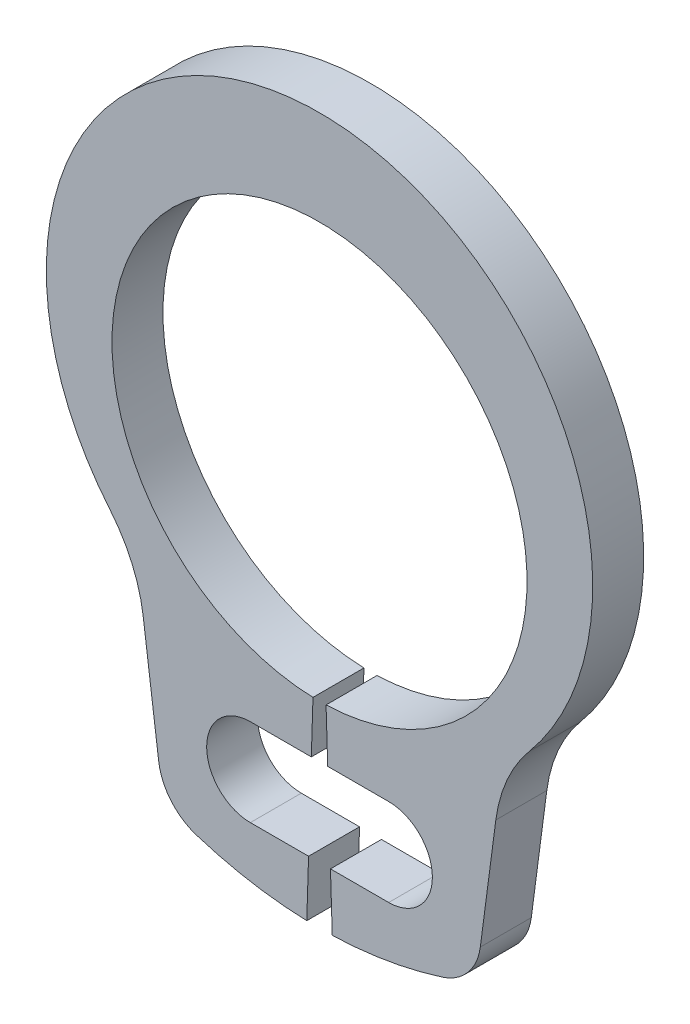
SolidWorks part; units mm, degrees
ref_plane "Plane1" through (0, 0, 0) normal (0, 0, 1) x (1, 0, 0)
ref_plane "Plane2" through (0, 0, 0) normal (0, 1, 0) x (1, 0, 0)
ref_plane "Plane3" through (0, 0, 0) normal (1, 0, 0) x (0, 0, -1)
other "Configuration Table"
sketch "Clipboard" plane through (0, 0, 0) normal (0, 0, 1) x (1, 0, 0)
  line L0 (0, 0) -> (1.3, 0)
  line L1 (0, 0) -> (0, 0.65)
  line L2 (0, 0) -> (0, -2.7)
  circle A0 centre (0, 0) radius 0.6
  circle A1 centre (0, 0) radius 3
  dimension "HoleDia" = 1.2
  dimension "ShaftDia" = 6
  dimension "LargeSection" = 1.3
  dimension "SmallSection" = 0.65
  dimension "LugSection" = 2.7
sketch "BodySke" plane through (0, 0, 0) normal (0, 0, 1) x (1, 0, 0)
  line L0 (-1.5431, 0) -> (1.5431, 0) construction
  line L1 (0, 0) -> (0, 4.15) construction
  line L2 (0.0899, -2.8486) -> (0.175, -5.5472)
  line L3 (-0.0899, -2.8486) -> (-0.175, -5.5472)
  line L4 (0, 0) -> (4.4489, -3.318) construction
  line L5 (0, 0) -> (-4.4489, -3.318) construction
  line L7 (2.4213, -3.0511) -> (2.2083, -4.669)
  line L8 (-2.4213, -3.0511) -> (-2.2083, -4.669)
  circle A0 centre (0, 0) radius 2.85 construction
  arc A1 (0.0899, -2.8486) -> (-0.0899, -2.8486) centre (0, 0) ccw
  arc A2 (2.8056, -2.0925) -> (-2.8056, -2.0925) centre (0, 0.3983) ccw construction
  arc A3 (0.175, -5.5472) -> (1.6935, -5.2853) centre (0, 0) ccw
  arc A4 (2.8793, -2.0069) -> (2.4213, -3.0511) centre (4.4489, -3.318) ccw
  arc A5 (-2.4213, -3.0511) -> (-2.8793, -2.0069) centre (-4.4489, -3.318) ccw
  arc A6 (-1.6935, -5.2853) -> (-0.175, -5.5472) centre (0, 0) ccw
  arc A7 (2.8793, -2.0069) -> (-2.8793, -2.0069) centre (0, 0.3983) ccw
  arc A8 (-2.353, -3.5691) -> (2.353, -3.5691) centre (0, 0) ccw construction
  circle A9 centre (0.95, -4.1681) radius 0.6
  circle A10 centre (-0.95, -4.1681) radius 0.6
  arc A11 (2.2083, -4.669) -> (1.6935, -5.2853) centre (1.4647, -4.5711) cw
  arc A12 (-2.2083, -4.669) -> (-1.6935, -5.2853) centre (-1.4647, -4.5711) ccw
  point P28 (2.1493, -5.1169)
  point P31 (-2.1493, -5.1169)
  dimension "HoleDia" = 1.2
  dimension "GrooveDia" = 5.7
  dimension "LugRad" = 5.55
  dimension "HoleOffsetRad" = 4.275
  dimension "D3" = 0.75
  dimension "LargeRad" = 4.15
  dimension "SmallRad" = 3.5
  dimension "SmallAngle" = 106.569
  dimension "D2" = 15
  dimension "HoleSpacing" = 1.9
  dimension "Gap" = 0.35
extrude "Body" add sketch "BodySke" against normal blind 0.7
sketch "NotSke" plane through (0, 0, 0) normal (0, 0, 1) x (1, 0, 0)
  line L0 (0.95, -3.5681) -> (0.95, -4.7681)
  line L1 (0.95, -4.7681) -> (-0.95, -4.7681)
  line L2 (-0.95, -4.7681) -> (-0.95, -3.5681)
  line L3 (-0.95, -3.5681) -> (0.95, -3.5681)
  circle A0 centre (0.95, -4.1681) radius 0.6 construction
  circle A1 centre (-0.95, -4.1681) radius 0.6 construction
extrude "Notch" cut sketch "NotSke" against normal through all
sketch "UnlSke" plane through (0, 0, 0) normal (0, 0, 1) x (1, 0, 0)
  line L0 (-1.9806, -5.1846) -> (-1.0171, -2.6623)
  line L1 (1.9806, -5.1846) -> (1.0171, -2.6623)
  arc A0 (1.0171, -2.6623) -> (-1.0171, -2.6623) centre (0, 0) ccw
  arc A1 (1.9806, -5.1846) -> (-1.9806, -5.1846) centre (0, 0) ccw
  arc A2 (0.175, -5.5472) -> (1.6935, -5.2853) centre (0, 0) ccw construction
  arc A3 (0.0899, -2.8486) -> (-0.0899, -2.8486) centre (0, 0) ccw construction
  circle A4 centre (-0.95, -4.1681) radius 0.6 construction
  circle A5 centre (0.95, -4.1681) radius 0.6 construction
extrude "Unlug" [suppressed] add sketch "UnlSke" against normal through all
equation "' \"ShaftDia@Clipboard\" = 3"
equation "' \"Thickness@Body\" = 0.4"
equation "' \"GrooveDia@BodySke\" = 2.8"
equation "' \"LugSection@Clipboard\" = 1.9"
equation "' \"LargeSection@Clipboard\" = 0.8"
equation "' \"HoleDia@Clipboard\" = 1.0"
equation "' \"ShaftDia@Clipboard\" = 10"
equation "' \"Thickness@Body\" = 1.0"
equation "' \"GrooveDia@BodySke\" = 9.6"
equation "' \"LugSection@Clipboard\" = 3.3"
equation "' \"LargeSection@Clipboard\" = 1.8"
equation "' \"HoleDia@Clipboard\" = 1.5"
equation "\"SmallSection@Clipboard\" = \"LargeSection@Clipboard\" * 0.5"
equation "\"Gap@BodySke\" =  \"Thickness@Body\" / 2"
equation "\"LargeRad@BodySke\" =  \"GrooveDia@BodySke\" / 2 +  \"LargeSection@Clipboard\""
equation "\"SmallRad@BodySke\" =  \"GrooveDia@BodySke\" / 2 +  \"SmallSection@Clipboard\""
equation "\"LugRad@BodySke\" = \"GrooveDia@BodySke\" / 2 + \"LugSection@Clipboard\""
equation "\"HoleOffsetRad@BodySke\" = (  \"ShaftDia@Clipboard\" / 2 + \"LugRad@BodySke\" ) / 2"
equation "\"HoleSpacing@BodySke\" = \"Gap@BodySke\"  * 2 +  \"HoleDia@Clipboard\""
equation "\"HoleDia@BodySke\" =  \"HoleDia@Clipboard\""
equation "\"SmallAngle@BodySke\" = atn(\"HoleSpacing@BodySke\" / 2 / sqr(\"HoleOffsetRad@BodySke\"  * \"HoleOffsetRad@BodySke\" - (\"HoleSpacing@BodySke\" / 2) * (\"HoleSpacing@BodySke\" / 2) ))  * 7 *  (\"LargeRad@BodySke\" / \"SmallRad@BodySke\")* ( 180 / 3.141593)"
